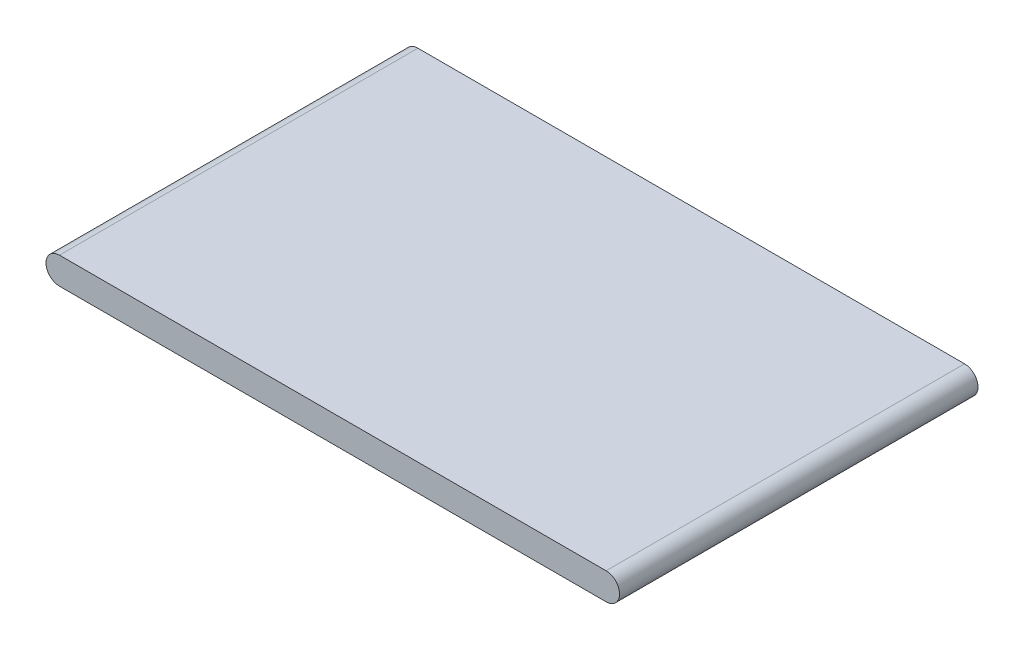
SolidWorks part; units mm, degrees
ref_plane "Front Plane" through (0, 0, 0) normal (0, 0, 1) x (1, 0, 0)
ref_plane "Top Plane" through (0, 0, 0) normal (0, 1, 0) x (1, 0, 0)
ref_plane "Right Plane" through (0, 0, 0) normal (1, 0, 0) x (0, 0, -1)
sketch "Sketch1" plane through (0, 0, 0) normal (0, 0, 1) x (1, 0, 0)
  line L0 (0, 0) -> (122, 0)
  line L2 (0, -6) -> (122, -6)
  arc A0 (0, 0) -> (0, -6) centre (0, -3) ccw
  arc A1 (122, -6) -> (122, 0) centre (122, -3) ccw
  dimension "D1" = 6
  dimension "D2" = 122
extrude "Boss-Extrude1" add sketch "Sketch1" along normal blind 80
ref_plane "Plane1" through (0, 0, 60) normal (0, 0, 1) x (1, 0, 0)
sketch "Sketch2" plane through (0, 0, 60) normal (0, 0, 1) x (1, 0, 0)
  line L0 (0, 0) -> (122, 0)
  line L1 (0, -6) -> (122, -6)
  line L2 (0, -6) -> (122, -6) construction
  arc A0 (122, -6) -> (122, 0) centre (122, -3) ccw construction
  arc A1 (0, 0) -> (0, -6) centre (0, -3) ccw construction
  arc A2 (122, 0) -> (122, -6) centre (122, -3) cw
  arc A3 (0, 0) -> (0, -6) centre (0, -3) ccw
